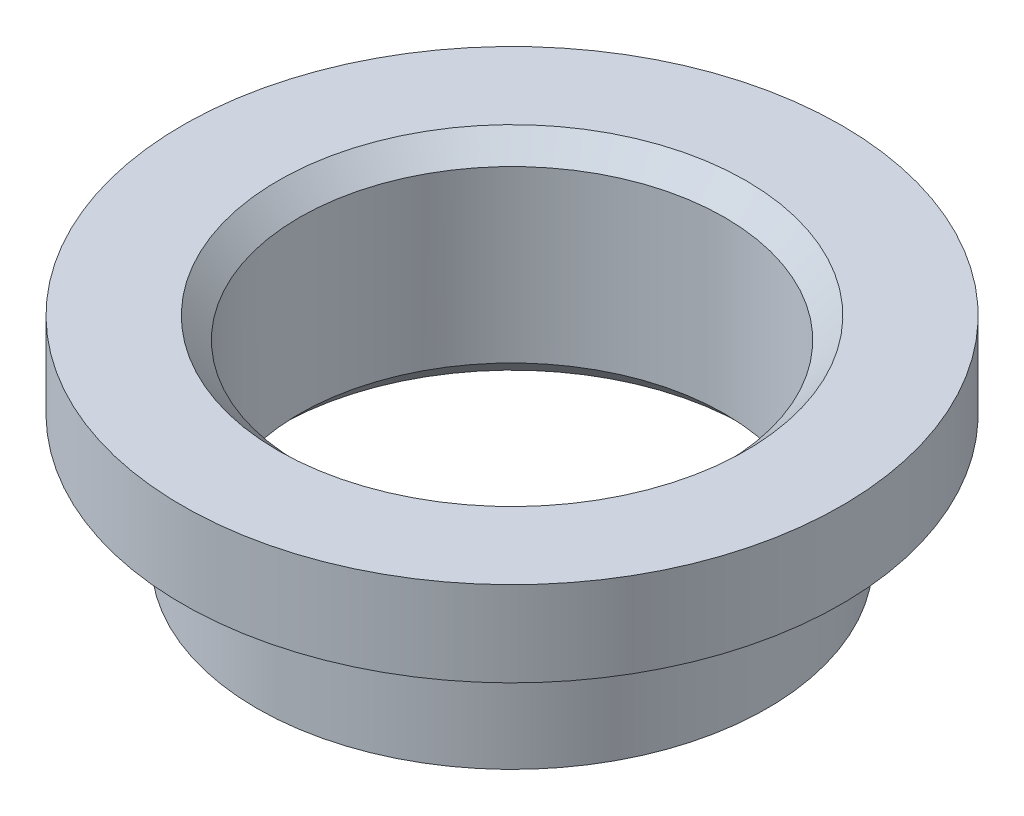
SolidWorks part; units mm, degrees
ref_plane "Front Plane" through (0, 0, 0) normal (0, 0, 1) x (1, 0, 0)
ref_plane "Top Plane" through (0, 0, 0) normal (0, 1, 0) x (1, 0, 0)
ref_plane "Right Plane" through (0, 0, 0) normal (1, 0, 0) x (0, 0, -1)
sketch "Sketch1" plane through (0, 0, 0) normal (0, 0, 1) x (1, 0, 0)
  line L0 (0, 0) -> (0, 84.1925) construction
  line L1 (5, 0) -> (5, -5)
  line L2 (5, -5) -> (6, -5)
  line L3 (6, -5) -> (6, -2)
  line L4 (6, -2) -> (7.75, -2)
  line L5 (7.75, -2) -> (7.75, 0)
  line L6 (7.75, 0) -> (5, 0)
  dimension "D1" = 12
  dimension "D2" = 5
  dimension "D3" = 2
  dimension "D4" = 15.5
  dimension "D5" = 1
revolve "Revolve1" add sketch "Sketch1" angle 360 about L0
chamfer "Chamfer1" distance 0.5 angle 45 2 edges at (0, -5, -5) (0, 0, -5)
